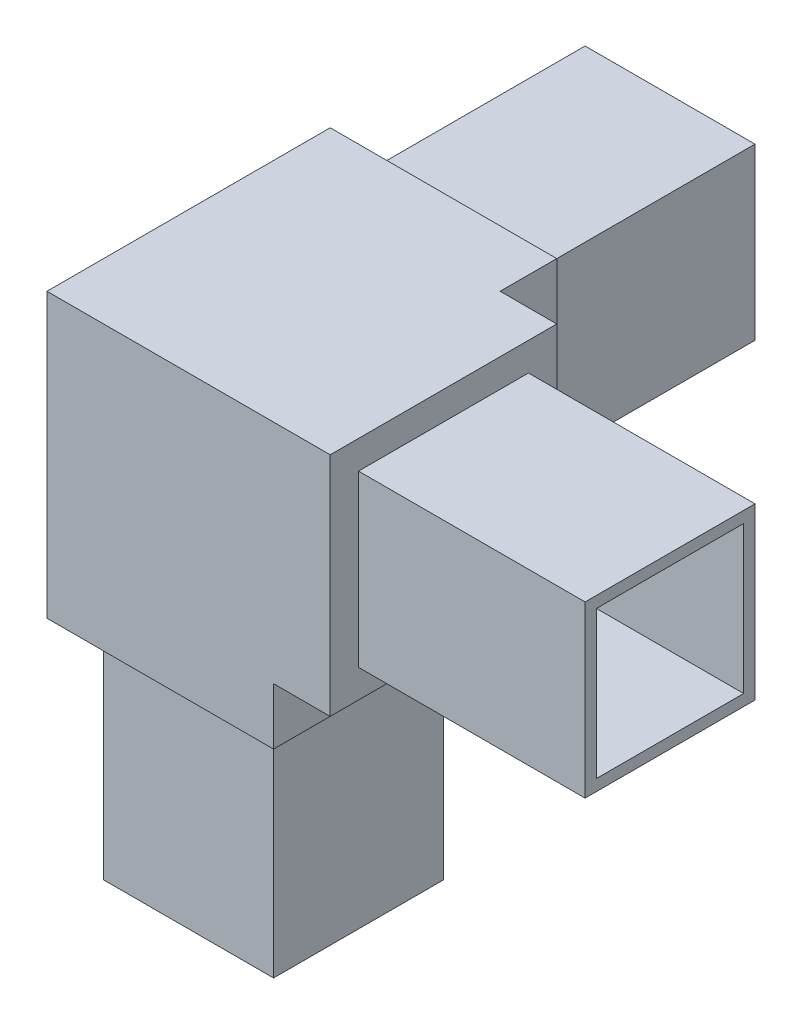
SolidWorks part; units mm, degrees
material "1060-H12"
ref_plane "Alzado" through (0, 0, 0) normal (0, 0, 1) x (1, 0, 0)
ref_plane "Planta" through (0, 0, 0) normal (0, 1, 0) x (1, 0, 0)
ref_plane "Vista lateral" through (0, 0, 0) normal (1, 0, 0) x (0, 0, -1)
sketch "Croquis1" plane through (0, 0, 0) normal (0, 1, 0) x (1, 0, 0)
  line L1 (20, -20) -> (-20, -20)
  line L2 (20, -20) -> (20, 20)
  line L3 (20, 20) -> (-20, 20)
  line L4 (-20, -20) -> (-20, 20)
  line L5 (20, -20) -> (-20, 20) construction
  line L6 (20, 20) -> (-20, -20) construction
  line L7 (20, -20) -> (70, -20)
  line L8 (20, -20) -> (20, 20)
  line L9 (20, 20) -> (70, 20)
  line L10 (70, -20) -> (70, 20)
  line L11 (-20, 20) -> (20, 20)
  line L12 (-20, 20) -> (-20, 70)
  line L13 (-20, 70) -> (20, 70)
  line L14 (20, 20) -> (20, 70)
  point P0 (0, 0)
  dimension "D1" = 40
  dimension "D2" = 40
  dimension "D3" = 50
  dimension "D4" = 50
extrude "Extruir1" add sketch "Croquis1" along normal blind 40 contours L3 L14 L13 L12 | L4 L1 L2 L3 | L7 L10 L9 L2
sketch "Croquis5" plane through (0, 0, 0) normal (0, -1, 0) x (1, 0, 0)
  line L1 (-20, 20) -> (20, 20)
  line L2 (-20, 20) -> (-20, -20)
  line L3 (-20, -20) -> (20, -20)
  line L4 (20, 20) -> (20, -20)
extrude "Extruir4" add sketch "Croquis5" along normal blind 50
sketch "Croquis2" plane through (70, 0, 0) normal (1, 0, 0) x (0, 0, -1)
  line L4 (-20, 0) -> (20, 0)
  line L5 (20, 0) -> (20, 40)
  line L6 (20, 40) -> (-20, 40)
  line L7 (-20, 40) -> (-20, 0)
  line L8 (-20, 0) -> (20, 0)
  line L9 (20, 0) -> (20, 40)
  line L10 (20, 40) -> (-20, 40)
  line L11 (-20, 40) -> (-20, 0)
  line L16 (-15, 5) -> (15, 5)
  line L17 (15, 5) -> (15, 35)
  line L18 (15, 35) -> (-15, 35)
  line L19 (-15, 35) -> (-15, 5)
  line L20 (-15, 5) -> (15, 5)
  line L21 (15, 5) -> (15, 35)
  line L22 (15, 35) -> (-15, 35)
  line L23 (-15, 35) -> (-15, 5)
  dimension "D1" = 0
  dimension "D2" = 5
extrude "Extruir2" cut sketch "Croquis2" against normal blind 40
sketch "Croquis3" plane through (0, 0, -70) normal (0, 0, -1) x (-1, 0, 0)
  line L0 (-15, 5) -> (15, 5)
  line L1 (15, 5) -> (15, 35)
  line L2 (15, 35) -> (-15, 35)
  line L3 (-15, 35) -> (-15, 5)
  line L4 (-20, 0) -> (20, 0)
  line L5 (20, 0) -> (20, 40)
  line L6 (20, 40) -> (-20, 40)
  line L7 (-20, 40) -> (-20, 0)
  line L8 (-20, 0) -> (20, 0)
  line L9 (20, 0) -> (20, 40)
  line L10 (20, 40) -> (-20, 40)
  line L11 (-20, 40) -> (-20, 0)
  dimension "D1" = 0
  dimension "D2" = 5
extrude "Extruir3" cut sketch "Croquis3" against normal blind 40
sketch "Croquis7" plane through (0, -50, 0) normal (0, -1, 0) x (1, 0, 0)
  line L0 (-15, 15) -> (-15, -15)
  line L1 (-15, -15) -> (15, -15)
  line L2 (15, -15) -> (15, 15)
  line L3 (15, 15) -> (-15, 15)
  line L4 (-20, 20) -> (-20, -20)
  line L5 (-20, -20) -> (20, -20)
  line L6 (20, -20) -> (20, 20)
  line L7 (20, 20) -> (-20, 20)
  line L8 (-20, 20) -> (-20, -20)
  line L9 (-20, -20) -> (20, -20)
  line L10 (20, -20) -> (20, 20)
  line L11 (20, 20) -> (-20, 20)
  dimension "D1" = 0
  dimension "D2" = 5
extrude "Extruir5" cut sketch "Croquis7" against normal blind 40
shell "Vaciado1" thickness 2
